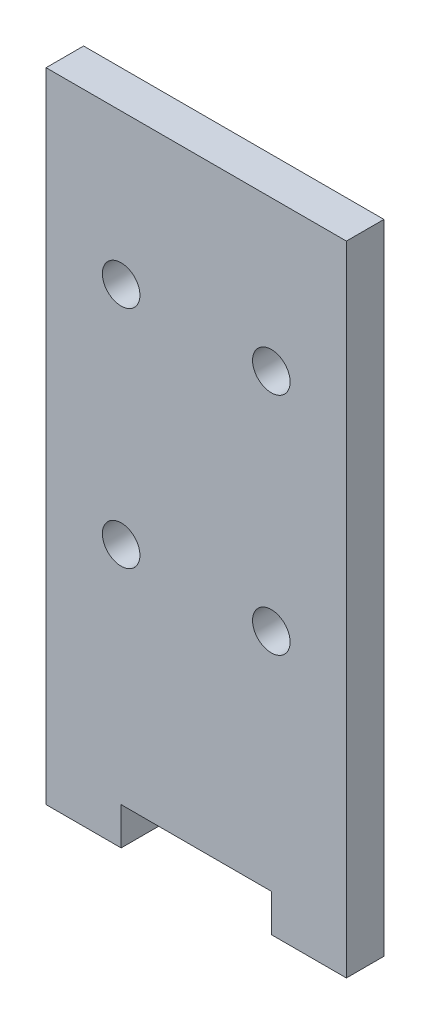
SolidWorks part; units mm, degrees
ref_plane "Front Plane" through (0, 0, 0) normal (0, 0, 1) x (1, 0, 0)
ref_plane "Top Plane" through (0, 0, 0) normal (0, 1, 0) x (1, 0, 0)
ref_plane "Right Plane" through (0, 0, 0) normal (1, 0, 0) x (0, 0, -1)
sketch "Sketch1" plane through (0, 0, 0) normal (0, 0, 1) x (1, 0, 0)
  line L0 (25.4, 101.6) -> (25.4, 0) construction
  line L1 (12.7, 0) -> (38.1, 0)
  line L2 (0, 0) -> (0, 101.6)
  line L3 (0, 101.6) -> (50.8, 101.6)
  line L4 (50.8, 0) -> (50.8, 101.6)
  line L6 (0, 0) -> (0, -6.35)
  line L7 (0, -6.35) -> (12.7, -6.35)
  line L8 (12.7, 0) -> (12.7, -6.35)
  line L9 (0, 50.8) -> (50.8, 50.8) construction
  line L10 (50.8, -6.35) -> (38.1, -6.35)
  line L11 (50.8, 0) -> (50.8, -6.35)
  line L12 (38.1, 0) -> (38.1, -6.35)
  circle A0 centre (12.7, 76.2) radius 3.175
  circle A1 centre (38.1, 76.2) radius 3.175
  circle A2 centre (12.7, 38.1) radius 3.175
  circle A3 centre (38.1, 38.1) radius 3.175
  dimension "D6" = 6.35
  dimension "D7" = 6.35
  dimension "D1" = 6.35
  dimension "D2" = 12.7
  dimension "D3" = 50.8
  dimension "D4" = 101.6
  dimension "D5" = 12.7
  dimension "D8" = 38.1
  dimension "D9" = 76.2
extrude "Boss-Extrude1" add sketch "Sketch1" along normal blind 6.35
sketch "Sketch2" plane through (0, 0, 6.35) normal (0, 0, 1) x (1, 0, 0)
  line L0 (12.7, 76.2) -> (38.1, 38.1) construction
  line L1 (12.7, 38.1) -> (38.1, 76.2) construction
  circle A0 centre (25.4, 57.15) radius 4.7625
  point P8 (25.4, 57.15)
  point P9 (-9.9, 75.6115)
  dimension "D1" = 9.525
equation "\"Wheel Thickness\"= 1in"
equation "\"Wheel Diameter\"= 3in"
equation "\"Motor Rear Diameter\" = 36.2mm"
equation "\"Motor Front Diameter\" = 12mm"
equation "\"Material Thickness\" = .25in"
equation "\"Wheel Cutout Diameter\"= 2cm"
equation "\"Motor Mount Tab Thickness\" = 100mm"
equation "\"Motor Mount Tab Height\" = 40mm"
equation "\"Motor Shaft Diameter\" = 3mm"
equation "\"Wheel Radius Clearance\" = 5mm"
equation "\"Wheel Cutout Width\" = 1.5in"
equation "\"Base Diameter\" = 10in"
equation "\"Wheel Mount Distance\" = 5mm"
equation "\"Motor Mount Distance\" = 50mm"
equation "\"Motor Cutout Length\" = 6in"
equation "\"Motor Cutout Height\" = 2in "
equation "\"Rod Diameter\" = 3/8in"
equation "\"Rod Length\" = 1.5in"
equation "\"Barrel Front Length\" = 1.8in"
equation "\"Barrerl Rear Length\" = 5in "
equation "\"Barrel Fillet Radius\" = 1in "
equation "\"Barrel Angle\" = 20deg"
equation "\"Barrel Diameter\" = 50mm"
equation "\"Barrel Shell Width\" = 2mm"
equation "\"Second Level Diameter\" = 10in"
equation "\"Ball Diameter\" = 40mm"
equation "\"Third Level Length\" = 9in"
equation "\"Third Level Height\" = 9in"
equation "\"Barrel Tab Clearance\" = 5mm"
equation "\"Barrel Tab Distance Away\" = 2mm"
equation "\"Hole Distance Apart\" = 2.8in"
equation "\"Barrel Tab Distance\"= 1.5in "
equation "\"Third Level Rod Distance\" = .5in"
equation " \"Second Rod Diameter\" = 3/8in"
equation "\"Second Rod Length\" = 3.88in"
equation "\"Bumper Wheel Clearance\" = 1.2in"
equation "\"Servo Tab Height\" = 4in"
equation "\"Servo Tab Width\" = 2in"
equation "\"Servo Tab Hole Horizontal Distance\" = 1in"
equation "\"Servo Tab Hole Vertical Distance\" = 1.5in "
equation "\"D1@Sketch1\"=\"Material Thickness\""
equation "\"D2@Sketch1\"=\"Servo Tab Width\"/4"
equation "\"D3@Sketch1\"=\"Servo Tab Width\""
equation "\"D4@Sketch1\"=\"Servo Tab Height\""
equation "\"Servo Hole Vertical Distance\" = 3in"
equation "\"D5@Sketch1\"=\"Servo Tab Hole Horizontal Distance\"/2"
equation "\"Servo Hole Diameter\" = 1/4in"
equation "\"D6@Sketch1\"=\"Servo Hole Diameter\""
equation "\"D7@Sketch1\"=\"Servo Hole Diameter\""
equation "\"D8@Sketch1\"=\"Servo Tab Hole Vertical Distance\""
equation "\"D1@Boss-Extrude1\"=\"Material Thickness\""
equation "\"D9@Sketch1\"=\"Servo Hole Vertical Distance\""
equation "\"Bumper Rod Length\"= 2in"
equation "\"Servo Shaft Diameter\"= 3/8in"
equation "\"D1@Sketch2\"=\"Servo Shaft Diameter\""
